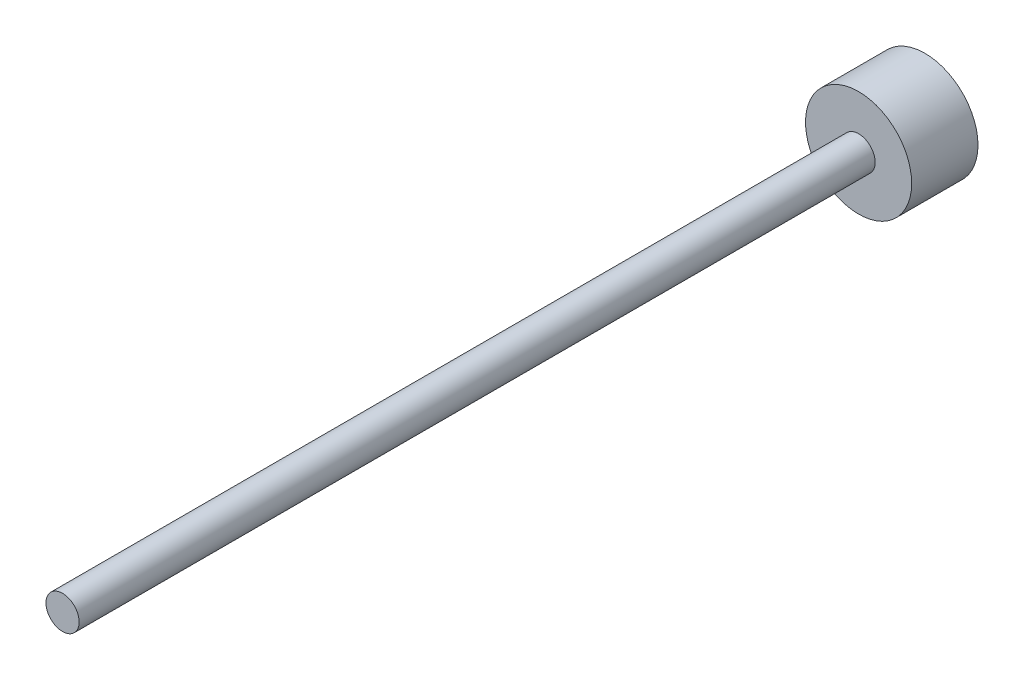
SolidWorks part; units mm, degrees
ref_plane "前视基准面" through (0, 0, 0) normal (0, 0, 1) x (1, 0, 0)
ref_plane "上视基准面" through (0, 0, 0) normal (0, 1, 0) x (1, 0, 0)
ref_plane "右视基准面" through (0, 0, 0) normal (1, 0, 0) x (0, 0, -1)
sketch "草图1" plane through (0, 0, 0) normal (0, 0, 1) x (1, 0, 0)
  circle A0 centre (0, 0) radius 8
extrude "凸台-拉伸1" add sketch "草图1" along normal blind 10
sketch "草图2" plane through (0, 0, 10) normal (0, 0, 1) x (1, 0, 0)
  circle A0 centre (0, 0) radius 2.5
extrude "凸台-拉伸2" add sketch "草图2" along normal blind 120
